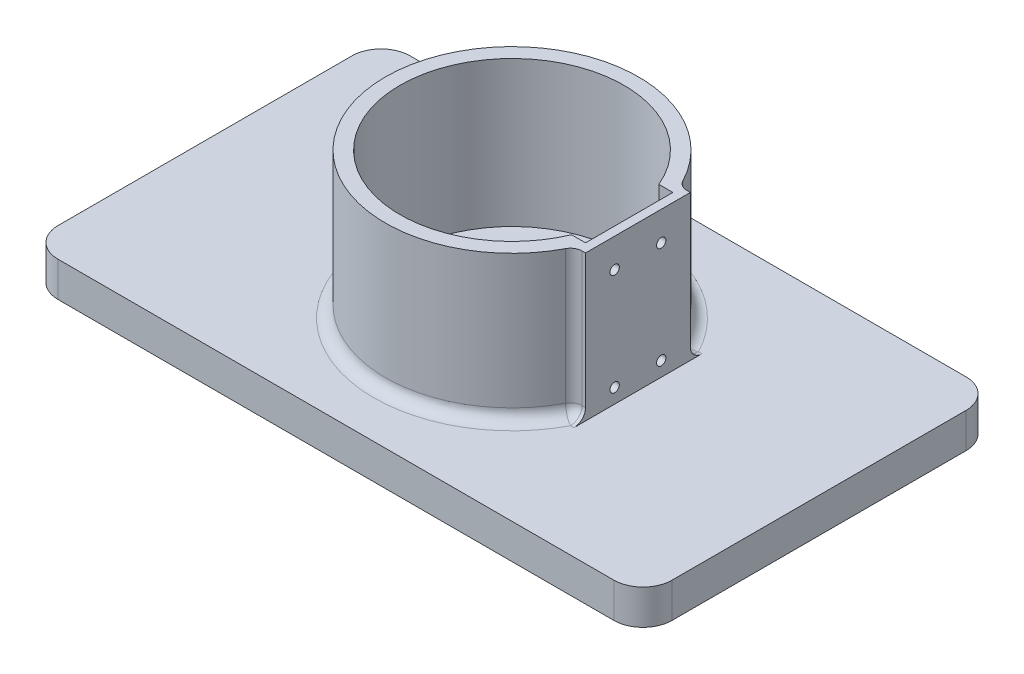
SolidWorks part; units mm, degrees
ref_plane "Front Plane" through (0, 0, 0) normal (0, 0, 1) x (1, 0, 0)
ref_plane "Top Plane" through (0, 0, 0) normal (0, 1, 0) x (1, 0, 0)
ref_plane "Right Plane" through (0, 0, 0) normal (1, 0, 0) x (0, 0, -1)
sketch "Sketch1" plane through (0, 0, 0) normal (0, 1, 0) x (1, 0, 0)
  line L1 (0, 0) -> (211, 0)
  line L2 (0, 0) -> (0, 121)
  line L3 (0, 121) -> (211, 121)
  line L4 (211, 0) -> (211, 121)
  dimension "D1" = 211
  dimension "D2" = 121
extrude "Boss-Extrude1" add sketch "Sketch1" along normal blind 12
sketch "Sketch2" plane through (0, 0, 0) normal (0, -1, 0) x (1, 0, 0)
  line L0 (0, -60.5) -> (5, -60.5) construction
  line L1 (5, -5) -> (206, -5)
  line L2 (5, -5) -> (5, -116)
  line L3 (5, -116) -> (206, -116)
  line L4 (206, -5) -> (206, -116)
  line L5 (0, -121) -> (0, 0) construction
  line L6 (105.5, 0) -> (105.5, -5) construction
  line L7 (0, 0) -> (211, 0) construction
  dimension "D1" = 5
  dimension "D2" = 5
extrude "Cut-Extrude1" cut sketch "Sketch2" against normal blind 7
sketch "Sketch3" plane through (0, 12, 0) normal (0, 1, 0) x (1, 0, 0)
  line L0 (0, 60.5) -> (105.5, 60.5) construction
  line L1 (0, 121) -> (0, 0) construction
  line L2 (105.5, 60.5) -> (105.5, 121) construction
  line L3 (211, 121) -> (0, 121) construction
  circle A0 centre (105.5, 60.5) radius 32
  dimension "D1" = 64
extrude "Cut-Extrude2" cut sketch "Sketch3" against normal through all
sketch "Sketch4" plane through (0, 12, 0) normal (0, 1, 0) x (1, 0, 0)
  line L3 (211, 0) -> (211, 121) construction
  line L4 (138.7754, 75.5) -> (211, 75.5)
  line L5 (138.7754, 75.5) -> (138.7754, 45.5)
  line L6 (138.7754, 45.5) -> (211, 45.5)
  line L7 (211, 75.5) -> (211, 45.5)
  line L8 (0, 60.5) -> (138.7754, 60.5) construction
  line L9 (0, 121) -> (0, 0) construction
  line L10 (145.7754, 75.5) -> (145.7754, 45.5)
  line L11 (148.7754, 78.5) -> (148.7754, 42.5)
  line L12 (145.1011, 78.5) -> (211, 78.5)
  line L14 (145.1011, 42.5) -> (211, 42.5)
  line L15 (211, 78.5) -> (211, 42.5)
  circle A0 centre (105.5, 60.5) radius 36.5 construction
  circle A1 centre (105.5, 60.5) radius 38.5
  circle A3 centre (105.5, 60.5) radius 32 construction
  arc A4 (148.7754, 64.9151) -> (148.7754, 56.0849) centre (105.5, 60.5) ccw
  dimension "D1" = 73
  dimension "D3" = 7
  dimension "D7" = 5
  dimension "D2" = 30
  dimension "D4" = 7
  dimension "D5" = 3
  dimension "D6" = 3
extrude "Boss-Extrude2" add sketch "Sketch4" along normal blind 50 contours A4 L6 A1 L4 | L6 A4 L11 L4 L10 | A4 L4 L11 L12 | A4 L11 L4 | A4 L6 L11 | A4 L14 L11 L6
sketch "Sketch5" plane through (148.7754, 0, 0) normal (1, 0, 0) x (0, 0, -1)
  line L0 (60.5, 62) -> (60.5, 52) construction
  line L1 (52.5, 52) -> (68.5, 52) construction
  line L2 (52.5, 52) -> (52.5, 17) construction
  line L3 (52.5, 17) -> (68.5, 17) construction
  line L4 (68.5, 52) -> (68.5, 17) construction
  line L9 (78.5, 62) -> (42.5, 62) construction
  line L10 (78.5, 12) -> (42.5, 12) construction
  circle A0 centre (52.5, 52) radius 1.6
  circle A1 centre (68.5, 52) radius 1.6
  circle A2 centre (68.5, 17) radius 1.6
  circle A3 centre (52.5, 17) radius 1.6
  point P6 (0, 0)
  point P7 (58, 62)
  dimension "D4" = 3.2
  dimension "D1" = 16
  dimension "D2" = 35
  dimension "D3" = 5
extrude "Cut-Extrude3" cut sketch "Sketch5" against normal blind 6
fillet "Fillet1" radius 4 5 edges at (146.9383, 12, -78.5) (146.9383, 12, -42.5) (62, 12, -60.5) (145.1011, 37, -78.5) (145.1011, 37, -42.5)
fillet "Fillet2" radius 10 8 edges at (206, 3.5, -5) (206, 3.5, -116) (211, 6, -121) (211, 6, 0) (5, 3.5, -5) (0, 6, 0) (0, 6, -121) (5, 3.5, -116)
